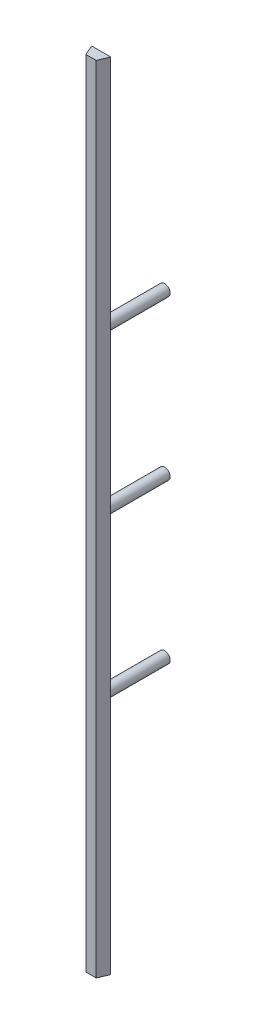
SolidWorks part; units mm, degrees
ref_plane "Front Plane" through (0, 0, 0) normal (0, 0, 1) x (1, 0, 0)
ref_plane "Top Plane" through (0, 0, 0) normal (0, 1, 0) x (1, 0, 0)
ref_plane "Right Plane" through (0, 0, 0) normal (1, 0, 0) x (0, 0, -1)
sketch "Sketch1" plane through (0, 0, 0) normal (0, 1, 0) x (1, 0, 0)
  line L0 (-31.4526, 0) -> (33.5474, 0)
  line L1 (33.5474, 0) -> (61.0474, 64.372)
  line L2 (61.0474, 64.372) -> (-58.9526, 64.372)
  line L3 (-58.9526, 64.372) -> (-31.4526, 0)
  dimension "D1" = 65
  dimension "D2" = 70
  dimension "D3" = 120
  dimension "D4" = 70
extrude "Boss-Extrude1" add sketch "Sketch1" along normal blind 5000
sketch "Sketch2" plane through (0, 0, -64.372) normal (0, 0, -1) x (-1, 0, 0)
  circle A0 centre (0, 1500) radius 35
  dimension "D1" = 70
  dimension "D2" = 1500
extrude "Boss-Extrude2" add sketch "Sketch2" along normal blind 400
pattern_linear "LPattern1" count 3 spacing 1000 along (0, 1, 0) of "Boss-Extrude2"
